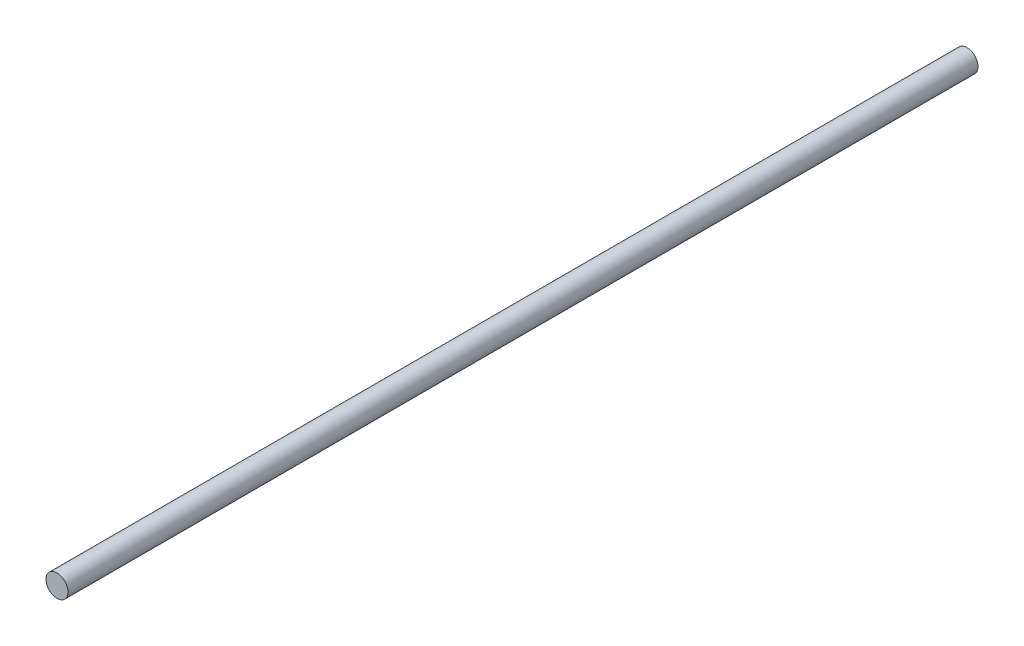
SolidWorks part; units mm, degrees
material "Plain Carbon Steel"
ref_plane "Спереди" through (0, 0, 0) normal (0, 0, 1) x (1, 0, 0)
ref_plane "Сверху" through (0, 0, 0) normal (0, 1, 0) x (1, 0, 0)
ref_plane "Справа" through (0, 0, 0) normal (1, 0, 0) x (0, 0, -1)
sketch "Sketch1" plane through (0, 0, 0) normal (0, 0, 1) x (1, 0, 0)
  circle A0 centre (0, 0) radius 4
  dimension "D1" = 8
extrude "Boss-Extrude1" add sketch "Sketch1" along normal blind 330
